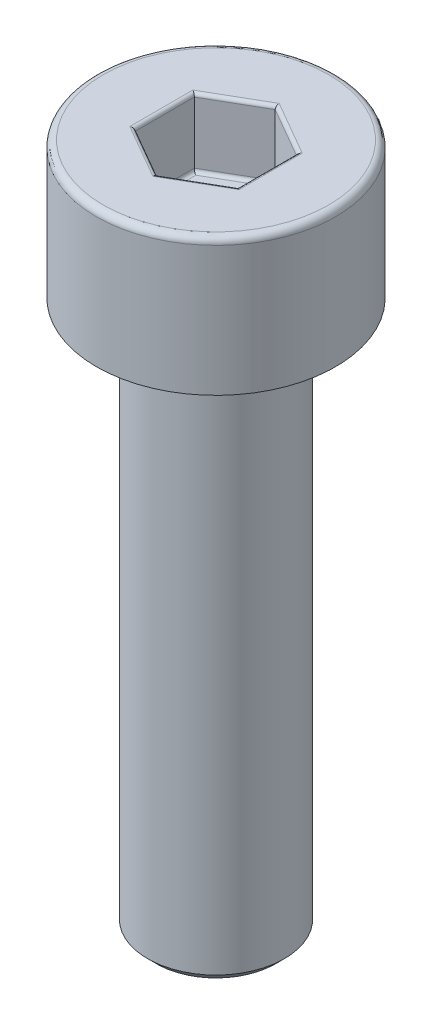
SolidWorks part; units mm, degrees
ref_plane "Front Plane" through (0, 0, 0) normal (0, 0, 1) x (1, 0, 0)
ref_plane "Top Plane" through (0, 0, 0) normal (0, 1, 0) x (1, 0, 0)
ref_plane "Right Plane" through (0, 0, 0) normal (1, 0, 0) x (0, 0, -1)
sketch "Sketch1" plane through (0, 0, 0) normal (0, 0, 1) x (1, 0, 0)
  line L0 (0, 0) -> (0, -47.0967) construction
  line L1 (0, -20) -> (-2, -20)
  line L2 (-2, -20) -> (-2, -4)
  line L3 (-2, -4) -> (-3.5, -4)
  line L4 (-3.5, -4) -> (-3.5, 0)
  line L5 (-3.5, 0) -> (0, 0)
  line L6 (0, 0) -> (0, -20)
  dimension "d" = 4
  dimension "l" = 20
  dimension "k" = 4
  dimension "dk" = 7
revolve "Revolve1" add sketch "Sketch1" angle 360 about L0
chamfer "Chamfer1" distance 0.25 angle 45 2 edges at (0, -4, 2) (0, -20, 2)
fillet "Fillet1" radius 0.2 1 edges at (0, 0, 3.5)
sketch "Sketch2" plane through (0, 0, 0) normal (0, 1, 0) x (1, 0, 0)
  line L1 (0, 1.7321) -> (-1.5, 0.866)
  line L2 (-1.5, 0.866) -> (-1.5, -0.866)
  line L3 (-1.5, -0.866) -> (0, -1.7321)
  line L4 (0, -1.7321) -> (1.5, -0.866)
  line L5 (1.5, -0.866) -> (1.5, 0.866)
  line L6 (1.5, 0.866) -> (0, 1.7321)
  circle A0 centre (0, 0) radius 1.5 construction
  dimension "s" = 3
extrude "Cut-Extrude1" cut sketch "Sketch2" against normal blind 2
fillet "Fillet2" radius 0.1 12 edges at (-0.75, 0, -1.299) (-1.5, 0, 0) (-0.75, 0, 1.299) (0.75, 0, 1.299) (1.5, 0, 0) (0.75, 0, -1.299) (1.5, -2, 0) (0.75, -2, 1.299) (-0.75, -2, 1.299) (-1.5, -2, 0) (-0.75, -2, -1.299) (0.75, -2, -1.299)
